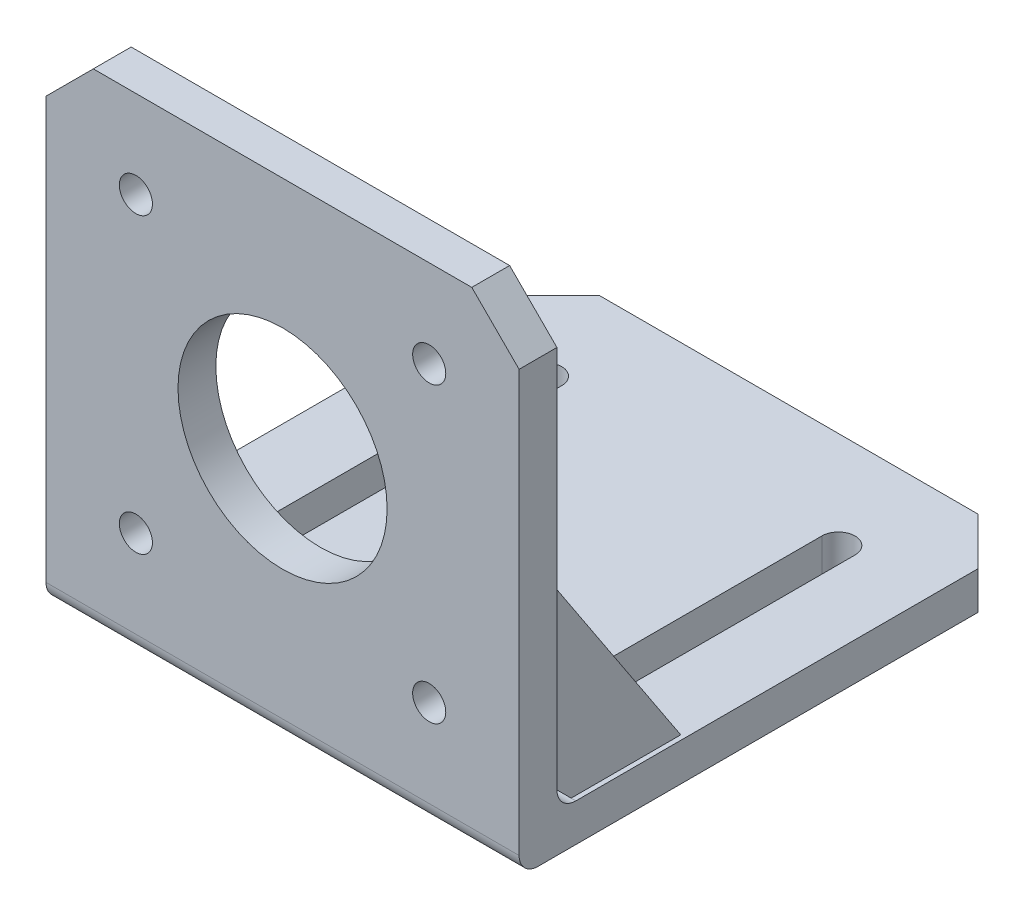
SolidWorks part; units mm, degrees
ref_plane "Alzado" through (0, 0, 0) normal (0, 0, 1) x (1, 0, 0)
ref_plane "Planta" through (0, 0, 0) normal (0, 1, 0) x (1, 0, 0)
ref_plane "Vista lateral" through (0, 0, 0) normal (1, 0, 0) x (0, 0, -1)
sketch "Croquis1" plane through (0, 0, 0) normal (1, 0, 0) x (0, 0, -1)
  line L1 (2, 0) -> (53.5, 0)
  line L3 (6, 4) -> (53.5, 4)
  line L4 (53.5, 0) -> (53.5, 4)
  line L6 (0, 2) -> (0, 51.5)
  line L7 (0, 51.5) -> (4, 51.5)
  line L8 (4, 6) -> (4, 51.5)
  arc A0 (6, 4) -> (4, 6) centre (6, 6) cw
  arc A1 (2, 0) -> (0, 2) centre (2, 2) cw
  dimension "D5" = 2
  dimension "D6" = 2
  dimension "D1" = 53.5
  dimension "D3" = 4
  dimension "D4" = 4
extrude "Saliente-Extruir1" add sketch "Croquis1" along normal blind 50
sketch "Croquis2" plane through (0, 0, 0) normal (0, 0, 1) x (1, 0, 0)
  line L0 (25, 51.5) -> (25, 0) construction
  line L1 (50, 51.5) -> (0, 51.5) construction
  line L2 (50, 0) -> (0, 0) construction
  line L3 (0, 26.75) -> (50, 26.75) construction
  line L4 (0, 51.5) -> (0, 2) construction
  line L5 (50, 51.5) -> (50, 2) construction
  line L6 (9.5, 51.5) -> (9.5, 0) construction
  line L7 (40.5, 51.5) -> (40.5, 0) construction
  line L8 (0, 42.25) -> (50, 42.25) construction
  line L9 (0, 11.25) -> (50, 11.25) construction
  circle A0 centre (25, 26.75) radius 11.05
  circle A1 centre (9.5, 42.25) radius 1.75
  circle A2 centre (40.5, 42.25) radius 1.75
  circle A3 centre (9.5, 11.25) radius 1.75
  circle A4 centre (40.5, 11.25) radius 1.75
  dimension "D1" = 22.1
  dimension "D3" = 3.5
  dimension "D2" = 31
extrude "Cortar-Extruir1" cut sketch "Croquis2" against normal through all
sketch "Croquis3" plane through (0, 0, 0) normal (0, -1, 0) x (1, 0, 0)
  line L0 (25, -2) -> (25, -53.5) construction
  line L1 (50, -2) -> (0, -2) construction
  line L2 (50, -53.5) -> (0, -53.5) construction
  line L3 (0, -27.75) -> (50, -27.75) construction
  line L4 (0, -2) -> (0, -53.5) construction
  line L5 (50, -2) -> (50, -53.5) construction
  line L6 (9.5, -2) -> (9.5, -53.5) construction
  line L7 (40.5, -2) -> (40.5, -53.5) construction
  line L8 (0, -12.25) -> (50, -12.25) construction
  line L9 (0, -43.25) -> (50, -43.25) construction
  line L10 (7.75, -12.25) -> (7.75, -43.25)
  line L11 (11.25, -12.25) -> (11.25, -43.25)
  line L12 (38.75, -12.25) -> (38.75, -43.25)
  line L13 (42.25, -12.25) -> (42.25, -43.25)
  arc A0 (11.25, -12.25) -> (7.75, -12.25) centre (9.5, -12.25) ccw
  arc A1 (42.25, -12.25) -> (38.75, -12.25) centre (40.5, -12.25) ccw
  arc A2 (7.75, -43.25) -> (11.25, -43.25) centre (9.5, -43.25) ccw
  arc A3 (38.75, -43.25) -> (42.25, -43.25) centre (40.5, -43.25) ccw
  dimension "D1" = 15.5
  dimension "D2" = 15.5
extrude "Cortar-Extruir2" cut sketch "Croquis3" against normal through all
chamfer "Chaflán1" distance 5 angle 45 4 edges at (0, 2, -53.5) (50, 2, -53.5) (50, 51.5, -2) (0, 51.5, -2)
ref_plane "Plano1" through (49.5, 0, 0) normal (1, 0, 0) x (0, 0, -1)
sketch "Croquis6" plane through (49.5, 0, 0) normal (1, 0, 0) x (0, 0, -1)
  line L0 (4, 6) -> (4, 46.5) construction
  line L1 (48.5, 4) -> (6, 4) construction
  line L2 (4, 24.5858) -> (4, 6)
  line L3 (4, 6) -> (6, 4)
  line L4 (6, 4) -> (17.5858, 4)
  line L5 (17.5858, 4) -> (4, 24.5858)
  arc A0 (4, 6) -> (6, 4) centre (6, 6) ccw construction
  arc A1 (4, 6) -> (6, 4) centre (6, 6) ccw construction
  point P0 (4, 24.5858)
  point P1 (17.5858, 4)
  point P9 (4.5858, 4.5858)
  point P10 (4.5858, 4.5858)
  dimension "D2" = 13
  dimension "D1" = 20
extrude "Saliente-Extruir4" add sketch "Croquis6" against normal blind 2
ref_plane "Plano2" through (0.5, 0, 0) normal (-1, 0, 0) x (0, 0, 1)
sketch "Croquis7" plane through (0.5, 0, 0) normal (-1, 0, 0) x (0, 0, 1)
  line L0 (-17.5858, 4) -> (-4, 24.5858)
  line L1 (-4, 24.5858) -> (-4, 6)
  line L2 (-4, 6) -> (-6, 4)
  line L3 (-6, 4) -> (-17.5858, 4)
extrude "Saliente-Extruir5" add sketch "Croquis7" against normal blind 2
ref_plane "Plano3" through (25, 0, 0) normal (-1, 0, 0) x (0, 0, 1)
